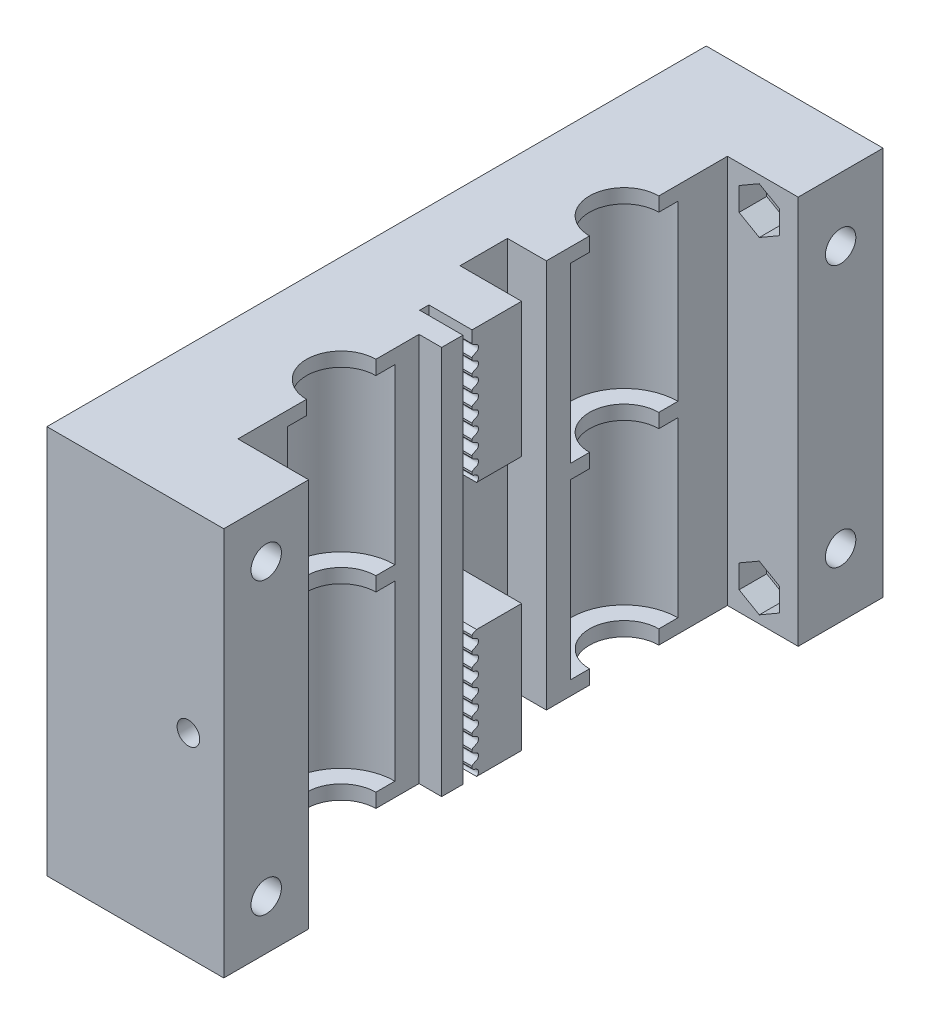
SolidWorks part; units mm, degrees
ref_plane "Front Plane" through (0, 0, 0) normal (0, 0, 1) x (1, 0, 0)
ref_plane "Top Plane" through (0, 0, 0) normal (0, 1, 0) x (1, 0, 0)
ref_plane "Right Plane" through (0, 0, 0) normal (1, 0, 0) x (0, 0, -1)
sketch "Sketch1" plane through (0, 0, 0) normal (0, 1, 0) x (1, 0, 0)
  line L0 (0, 36.6) -> (0, 43.6)
  line L1 (0, 43.6) -> (10, 43.6)
  line L2 (10, 43.6) -> (10, 55.6)
  line L3 (10, 55.6) -> (-15, 55.6)
  line L5 (-15, -37.6) -> (10, -37.6)
  line L6 (10, -37.6) -> (10, -25.6)
  line L7 (10, -25.6) -> (0, -25.6)
  line L8 (0, -25.6) -> (0, -18.6)
  line L9 (0, 21.4) -> (0, -3.4) construction
  line L10 (0, 18) -> (-5.5, 18)
  line L11 (-5.5, 18) -> (-5.5, 0)
  line L12 (-5.5, 0) -> (0, 0)
  line L24 (-15, 55.6) -> (-15, -37.6)
  line L25 (0, 0) -> (0, -3.4)
  line L26 (0, 18) -> (0, 21.4)
  arc A1 (0, 21.4) -> (0, 36.6) centre (0, 29) cw
  arc A2 (0, -18.6) -> (0, -3.4) centre (0, -11) cw
  dimension "D2" = 7.6
  dimension "D3" = 7.6
  dimension "D4" = 7
  dimension "D5" = 7
  dimension "D6" = 12
  dimension "D7" = 12
  dimension "D8" = 18
  dimension "D9" = 10
  dimension "D10" = 10
  dimension "D11" = 5.5
  dimension "D12" = 3.4
  dimension "D13" = 3.4
  dimension "D14" = 25
  dimension "D15" = 40
extrude "Boss-Extrude1" add sketch "Sketch1" along normal blind 55
sketch "Sketch2" plane through (0, 0, 0) normal (0, -1, 0) x (1, 0, 0)
  line L0 (0, 18.6) -> (0, 15.9)
  line L1 (0, 6.1) -> (0, 3.4)
  line L2 (0, -21.4) -> (0, -24.102)
  line L3 (0, -33.898) -> (0, -36.6)
  arc A0 (0, 3.4) -> (0, 18.6) centre (0, 11) cw
  arc A1 (0, 6.1) -> (0, 15.9) centre (0, 11) cw
  arc A2 (0, -36.6) -> (0, -21.4) centre (0, -29) cw
  arc A3 (0, -33.898) -> (0, -24.102) centre (0, -29) cw
  dimension "D1" = 4.9
  dimension "D2" = 4.898
extrude "Boss-Extrude2" add sketch "Sketch2" against normal blind 2
ref_plane "Plane1" through (0, 26.5, 0) normal (0, -1, 0) x (-1, 0, 0)
sketch "Sketch3" plane through (0, 26.5, 0) normal (0, -1, 0) x (-1, 0, 0)
  line L0 (0, -3.4) -> (0, -6.1)
  line L1 (0, -15.9) -> (0, -18.6)
  line L2 (0, 21.4) -> (0, 24.1)
  line L3 (0, 33.9) -> (0, 36.6)
  arc A0 (0, -18.6) -> (0, -3.4) centre (0, -11) ccw
  arc A1 (0, -15.9) -> (0, -6.1) centre (0, -11) ccw
  arc A2 (0, 36.6) -> (0, 21.4) centre (0, 29) cw
  arc A3 (0, 24.1) -> (0, 33.9) centre (0, 29) ccw
  dimension "D1" = 4.9
extrude "Boss-Extrude3" add sketch "Sketch3" against normal blind 2
ref_plane "Plane2" through (0, 53, 0) normal (0, -1, 0) x (-1, 0, 0)
sketch "Sketch4" plane through (0, 53, 0) normal (0, -1, 0) x (-1, 0, 0)
  line L0 (0, -18.6) -> (0, -15.9)
  line L1 (0, -6.1) -> (0, -3.4)
  line L2 (0, 36.6) -> (0, 33.9)
  line L3 (0, 24.1) -> (0, 21.4)
  arc A0 (0, -3.4) -> (0, -18.6) centre (0, -11) cw
  arc A1 (0, -15.9) -> (0, -6.1) centre (0, -11) ccw
  arc A2 (0, -15.9) -> (0, -6.1) centre (0, -11) ccw construction
  arc A3 (0, 21.4) -> (0, 36.6) centre (0, 29) ccw construction
  arc A5 (0, 24.1) -> (0, 33.9) centre (0, 29) ccw
  arc A6 (0, 21.4) -> (0, 36.6) centre (0, 29) ccw
  arc A7 (0, 24.1) -> (0, 33.9) centre (0, 29) ccw construction
extrude "Boss-Extrude4" add sketch "Sketch4" against normal blind 2
sketch "Sketch7" plane through (0, 55, 0) normal (0, 1, 0) x (1, 0, 0)
  line L0 (0, 0) -> (3.2, 0)
  line L1 (3.2, 0) -> (3.2, -2)
  line L2 (3.2, -2) -> (0, -2)
  line L3 (0, -6.1) -> (0, 0) construction
  line L4 (0, -2) -> (0, 0)
  dimension "D1" = 2
  dimension "D2" = 3.2
extrude "Boss-Extrude5" add sketch "Sketch7" against normal up to surface (55 mm away) up to face at (-0.6749, 0, -9)
sketch "Sketch8" plane through (0, 55, 0) normal (0, 1, 0) x (1, 0, 0)
  line L0 (0, 18) -> (0, 0) construction
  line L1 (-3.9424, 9) -> (6.0186, 9) construction
  line L2 (-5.5, 0) -> (3.2, 0)
  line L3 (3.2, 0) -> (-5.5, 0) construction
  line L4 (3.2, 0) -> (3.2, 3)
  line L5 (3.2, 3) -> (-5.5, 3)
  line L6 (-5.5, 0) -> (-5.5, 18) construction
  line L7 (-5.5, 3) -> (-5.5, 0)
  line L8 (3.2, -2) -> (3.2, 0) construction
  line L9 (-5.5, 11.3) -> (3.2, 11.3)
  line L10 (3.2, 11.3) -> (3.2, 4.3)
  line L11 (3.2, 4.3) -> (-5.5, 4.3)
  line L12 (-5.5, 4.3) -> (-5.5, 11.3)
  point P6 (0, 9)
  dimension "D1" = 3
  dimension "D2" = 7
  dimension "D3" = 1.3
extrude "Boss-Extrude6" add sketch "Sketch8" against normal up to surface (55 mm away) up to face at (-0.2443, 0, -7.7778)
sketch "Sketch11" plane through (3.2, 0, 0) normal (1, 0, 0) x (0, 0, -1)
  line L0 (1264.5675, 560.6102) -> (1262.5675, 560.6102) construction
  line L1 (4.3, 0) -> (4.3, 55) construction
  line L2 (4.2853, 45.4328) -> (4.2853, 47.4569)
  spline S0 degree 3 poles (4.2853, 47.4569) (4.284, 47.4147) (4.2867, 47.3463) (4.3158, 47.2523) (4.3712, 47.1708) (4.4771, 47.1012) (4.6041, 47.0544) (4.7214, 46.9971) (4.8254, 46.9474) (4.9241, 46.9047) (5.0186, 46.8525) (5.1086, 46.7783) (5.1561, 46.6816) (5.1905, 46.5926) (5.1913, 46.5195) (5.1931, 46.4561) (5.1891, 46.3829) (5.1871, 46.2871) (5.1399, 46.1709) (5.0494, 46.057) (4.9087, 45.9856) (4.7554, 45.916) (4.621, 45.8529) (4.5075, 45.8004) (4.4122, 45.7562) (4.3028, 45.6419) (4.2855, 45.5136) (4.2853, 45.4328) knots 0 0 0 0 0.042789 0.068472 0.09859 0.140403 0.193951 0.235463 0.272242 0.310543 0.344117 0.381404 0.42616 0.451184 0.477135 0.499165 0.515432 0.551275 0.595353 0.639476 0.695379 0.752126 0.810504 0.845135 0.878871 0.916023 1 1 1 1
  line M5 (4.3, 55) -> (4.3, 0)
  dimension "D1" = 2
extrude "Cut-Extrude4" cut sketch "Sketch11" against normal up to surface (8.7 mm away) contours S0 M5 up to face at (-5.5, 27.5, -3.65)
pattern_linear "LPattern1" count 24 spacing 2 along (0, 1, 0) count 4 spacing 2 along (0, 1, 0) of "Cut-Extrude4"
sketch "Sketch12" plane through (3.2, 0, 0) normal (1, 0, 0) x (0, 0, -1)
  line L0 (11.3, 0) -> (11.3, 55) construction
  line L1 (11.3, 36) -> (4.3, 36)
  line L2 (11.3, 36) -> (11.3, 18)
  line L3 (11.3, 18) -> (4.3, 18)
  line L4 (4.3, 36) -> (4.3, 18)
  dimension "D1" = 18
  dimension "D2" = 19
extrude "Cut-Extrude5" cut sketch "Sketch12" against normal up to surface (8.7 mm away) up to face at (-5.5, 27.5, -14.65)
sketch "Sketch13" plane through (0, 55, 0) normal (0, 1, 0) x (1, 0, 0)
  line L0 (-5.5, 3) -> (-2.9059, 3)
  line L1 (3.2, 3) -> (-5.5, 3) construction
  line L6 (-2.9059, 3) -> (-2.9059, 7.169)
  line L7 (-2.9059, 7.169) -> (-5.5, 7.169)
  line L8 (-5.5, 18) -> (-5.5, 0) construction
  line L9 (-5.5, 7.169) -> (-5.5, 3)
extrude "Boss-Extrude16" add sketch "Sketch13" against normal up to surface (55 mm away) up to face at (-0.409, 0, -8.1123)
sketch "Sketch14" plane through (0, 55, 0) normal (0, 1, 0) x (1, 0, 0)
  line L0 (0, 0) -> (0, -2)
  line L1 (0, -2) -> (3.2, -2)
  line L2 (3.2, -2) -> (3.2, 0)
  line L3 (3.2, -2) -> (3.2, 3) construction
  line L4 (3.2, 0) -> (0, 0)
extrude "Cut-Extrude6" cut sketch "Sketch14" against normal up to surface (55 mm away) up to face at (-0.1732, 0, -8.1123)
sketch "Sketch16" plane through (-2.9059, 0, 0) normal (1, 0, 0) x (0, 0, -1)
  line L0 (7.169, 36) -> (3, 36)
  line L1 (3, 0) -> (3, 55) construction
  line L2 (7.169, 18) -> (3, 18)
  line L3 (3, 18) -> (3, 36)
  line L4 (7.169, 36) -> (7.169, 18)
extrude "Cut-Extrude7" cut sketch "Sketch16" against normal up to surface (2.5941 mm away) up to face at (-5.5, 27.25, -11.9423)
sketch "Sketch17" plane through (-15, 0, 0) normal (-1, 0, 0) x (0, 0, 1)
  line L0 (-55.6, 55) -> (37.6, 55) construction
  line L1 (37.6, 55) -> (37.6, 0) construction
  line L2 (37.6, 0) -> (25.6, 0) construction
  line L3 (-36.6, 0) -> (-43.6, 0) construction
  line L4 (-55.6, 55) -> (-55.6, 0) construction
  circle A0 centre (31.6, 48) radius 2.15
  circle A1 centre (31.6, 7) radius 2.15
  circle A2 centre (-49.6, 9) radius 2.15
  circle A3 centre (-49.6, 46) radius 2.15
  dimension "D1" = 4.3
  dimension "D2" = 4.3
  dimension "D3" = 4.3
  dimension "D4" = 4.3
  dimension "D6" = 6
  dimension "D7" = 7
  dimension "D5" = 7
  dimension "D8" = 6
  dimension "D9" = 9
  dimension "D10" = 6
  dimension "D11" = 6
  dimension "D12" = 9
extrude "Cut-Extrude8" cut sketch "Sketch17" against normal up to surface (25 mm away) up to face at (10, 27.5, 31.6)
ref_plane "Plane3" through (-11.9, 0, 0) normal (-1, 0, 0) x (0, 0, 1)
sketch "Sketch20" plane through (-5.5, 0, 0) normal (1, 0, 0) x (0, 0, -1)
  line L0 (55.6, 55) -> (-37.6, 55) construction
  line L1 (55.6, 55) -> (55.6, 0) construction
  circle A0 centre (9, 27.5) radius 2.7
  dimension "D1" = 5.4
  dimension "D2" = 27.5
  dimension "D3" = 46.6
extrude "Cut-Extrude9" cut sketch "Sketch20" against normal up to surface (9.5 mm away) up to face at (-15, 46, -47.45)
sketch "Sketch21" plane through (0, 0, -43.6) normal (0, 0, 1) x (1, 0, 0)
  line L0 (10, 55) -> (10, 0) construction
  line L1 (4.5, 47.3091) -> (7.35, 48.9546)
  line L2 (7.35, 48.9546) -> (7.35, 52.2454)
  line L3 (7.35, 52.2454) -> (4.5, 53.8909)
  line L4 (4.5, 53.8909) -> (1.65, 52.2454)
  line L5 (1.65, 52.2454) -> (1.65, 48.9546)
  line L6 (1.65, 48.9546) -> (4.5, 47.3091)
  line L7 (0, 55) -> (10, 55) construction
  circle A0 centre (4.5, 50.6) radius 2.85 construction
  dimension "D2" = 4.4
  dimension "D3" = 5.5
  dimension "D1" = 5.7
ref_plane "Plane4" through (0, 27.5, 0) normal (0, 1, 0) x (1, 0, 0)
extrude "Cut-Extrude10" cut sketch "Sketch21" against normal blind 3.9
sketch "Sketch23" plane through (0, 0, -47.5) normal (0, 0, 1) x (1, 0, 0)
  line L0 (0, 55) -> (10, 55) construction
  line L1 (10, 55) -> (10, 0) construction
  circle A0 centre (4.5, 50.6) radius 1.6
  dimension "D1" = 3.2
  dimension "D2" = 4.4
  dimension "D3" = 5.5
extrude "Cut-Extrude11" cut sketch "Sketch23" against normal up to surface (8.1 mm away) up to face at (-2.5, 27.5, -55.6)
mirror "Mirror1" about plane through (0, 27.5, 0) normal (0, 1, 0) of "Cut-Extrude11", "Cut-Extrude10"
sketch "Sketch26" plane through (0, 0, 25.6) normal (0, 0, -1) x (-1, 0, 0)
  line L0 (-10, 55) -> (-10, 0) construction
  line L1 (-5, 24.2091) -> (-2.15, 25.8546)
  line L2 (-2.15, 25.8546) -> (-2.15, 29.1454)
  line L3 (-2.15, 29.1454) -> (-5, 30.7909)
  line L4 (-5, 30.7909) -> (-7.85, 29.1454)
  line L5 (-7.85, 29.1454) -> (-7.85, 25.8546)
  line L6 (-7.85, 25.8546) -> (-5, 24.2091)
  line L7 (-10, 0) -> (0, 0) construction
  circle A0 centre (-5, 27.5) radius 2.85 construction
  dimension "D1" = 27.5
  dimension "D2" = 5
  dimension "D3" = 5.7
extrude "Cut-Extrude12" cut sketch "Sketch26" against normal blind 4
sketch "Sketch27" plane through (0, 0, 29.6) normal (0, 0, -1) x (-1, 0, 0)
  line L0 (-10, 55) -> (-10, 0) construction
  line L1 (-10, 55) -> (0, 55) construction
  circle A0 centre (-5, 27.5) radius 1.6
  dimension "D3" = 3.2
  dimension "D1" = 5
  dimension "D2" = 27.5
extrude "Cut-Extrude13" cut sketch "Sketch27" against normal up to surface (8 mm away) up to face at (-2.5, 27.5, 37.6)
sketch "Sketch28" plane through (-15, 0, 0) normal (-1, 0, 0) x (0, 0, 1)
  line L0 (-55.6, 55) -> (-55.6, 0) construction
  line L1 (-45.95, 11.1073) -> (-49.6, 13.2147)
  line L2 (-49.6, 13.2147) -> (-53.25, 11.1073)
  line L3 (-53.25, 11.1073) -> (-53.25, 6.8927)
  line L4 (-53.25, 6.8927) -> (-49.6, 4.7853)
  line L5 (-49.6, 4.7853) -> (-45.95, 6.8927)
  line L6 (-45.95, 6.8927) -> (-45.95, 11.1073)
  circle A0 centre (-49.6, 9) radius 3.65 construction
  dimension "D1" = 7.3
extrude "Cut-Extrude14" cut sketch "Sketch28" against normal blind 4
pattern_linear "LPattern4" count 2 spacing 37 along (0, 1, 0) of "Cut-Extrude14"
sketch "Sketch29" plane through (-15, 0, 0) normal (-1, 0, 0) x (0, 0, 1)
  line L0 (37.6, 55) -> (37.6, 0) construction
  line L1 (31.6, 11.2147) -> (27.95, 9.1073)
  line L2 (27.95, 9.1073) -> (27.95, 4.8927)
  line L3 (27.95, 4.8927) -> (31.6, 2.7853)
  line L4 (31.6, 2.7853) -> (35.25, 4.8927)
  line L5 (35.25, 4.8927) -> (35.25, 9.1073)
  line L6 (35.25, 9.1073) -> (31.6, 11.2147)
  circle A0 centre (31.6, 7) radius 3.65 construction
  point P11 (35.25, 7)
  dimension "D1" = 7.3
extrude "Cut-Extrude15" cut sketch "Sketch29" against normal blind 4
pattern_linear "LPattern5" count 2 spacing 41 along (0, 1, 0) of "Cut-Extrude15"
ref_plane "Plane5" through (0, 0, -53.7) normal (0, 0, -1) x (-1, 0, 0)
